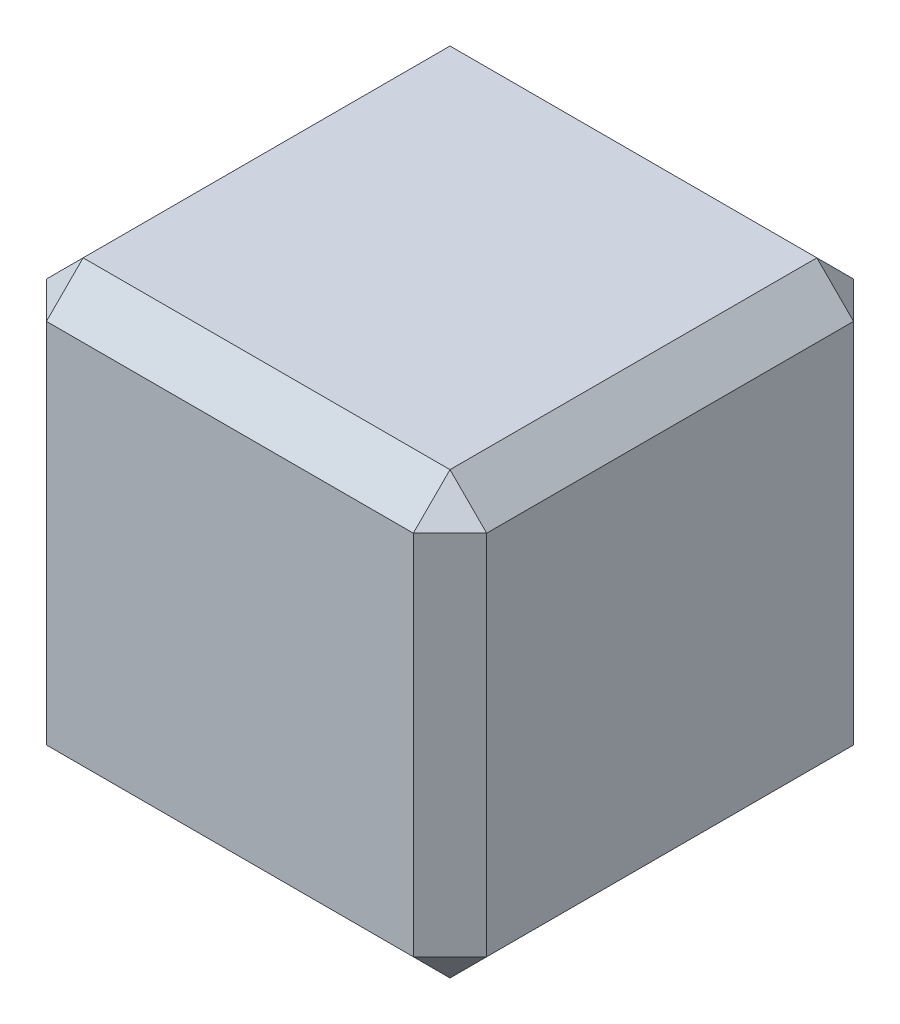
SolidWorks part; units mm, degrees
ref_plane "Front Plane" through (0, 0, 0) normal (0, 0, 1) x (1, 0, 0)
ref_plane "Top Plane" through (0, 0, 0) normal (0, 1, 0) x (1, 0, 0)
ref_plane "Right Plane" through (0, 0, 0) normal (1, 0, 0) x (0, 0, -1)
sketch "Sketch1" plane through (0, 0, 0) normal (0, 1, 0) x (1, 0, 0)
  line L1 (-3, 3) -> (3, 3)
  line L2 (-3, 3) -> (-3, -3)
  line L3 (-3, -3) -> (3, -3)
  line L4 (3, 3) -> (3, -3)
  line L5 (-3, 3) -> (3, -3) construction
  line L6 (-3, -3) -> (3, 3) construction
  point P0 (0, 0)
  dimension "D1" = 6
extrude "Boss-Extrude1" add sketch "Sketch1" along normal mid plane 6
chamfer "Chamfer1" distance 0.5 angle 45 12 edges at (0, -3, -3) (-3, -3, 0) (-3, 0, -3) (-3, 0, 3) (3, 0, -3) (0, -3, 3) (3, -3, 0) (3, 0, 3) (0, 3, -3) (-3, 3, 0) (3, 3, 0) (0, 3, 3)
